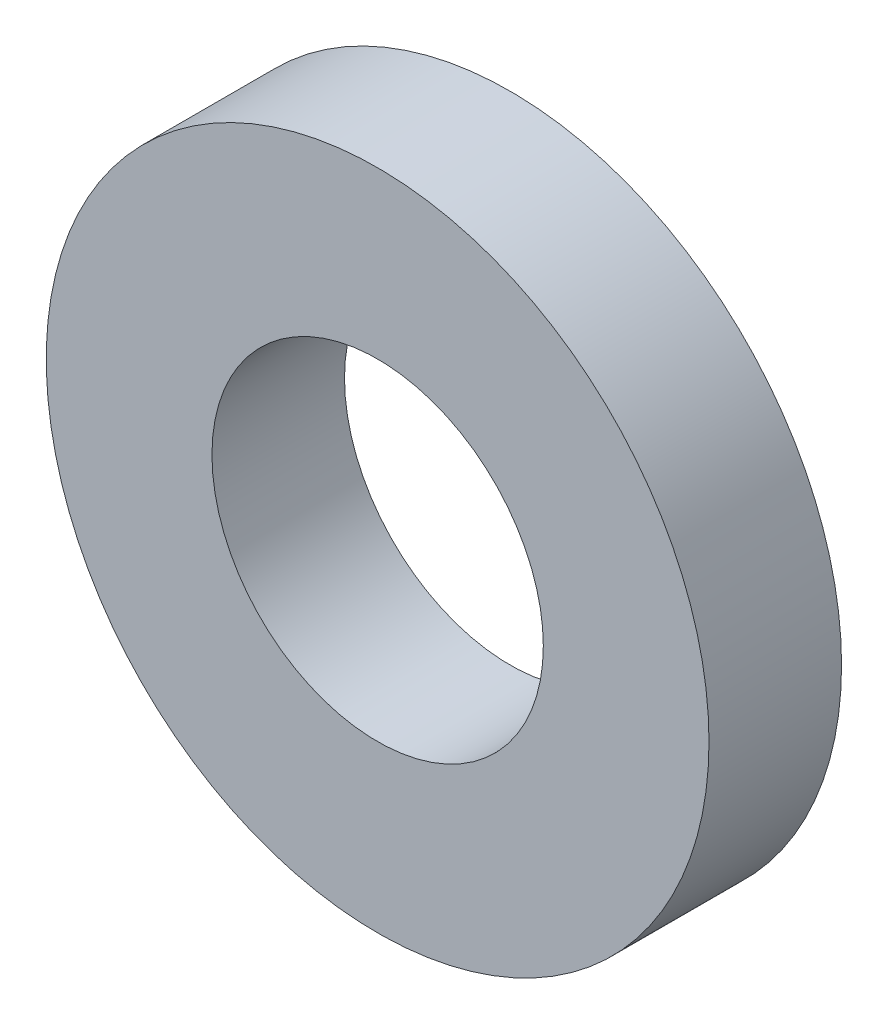
SolidWorks part; units mm, degrees
ref_plane "Front Plane" through (0, 0, 0) normal (0, 0, 1) x (1, 0, 0)
ref_plane "Top Plane" through (0, 0, 0) normal (0, 1, 0) x (1, 0, 0)
ref_plane "Right Plane" through (0, 0, 0) normal (1, 0, 0) x (0, 0, -1)
sketch "Sketch1" plane through (0, 0, 0) normal (0, 0, 1) x (1, 0, 0)
  circle A0 centre (0, 0) radius 1.5
  circle A1 centre (0, 0) radius 3
  dimension "D1" = 3
  dimension "D2" = 6
extrude "Boss-Extrude1" add sketch "Sketch1" along normal mid plane 1.2
